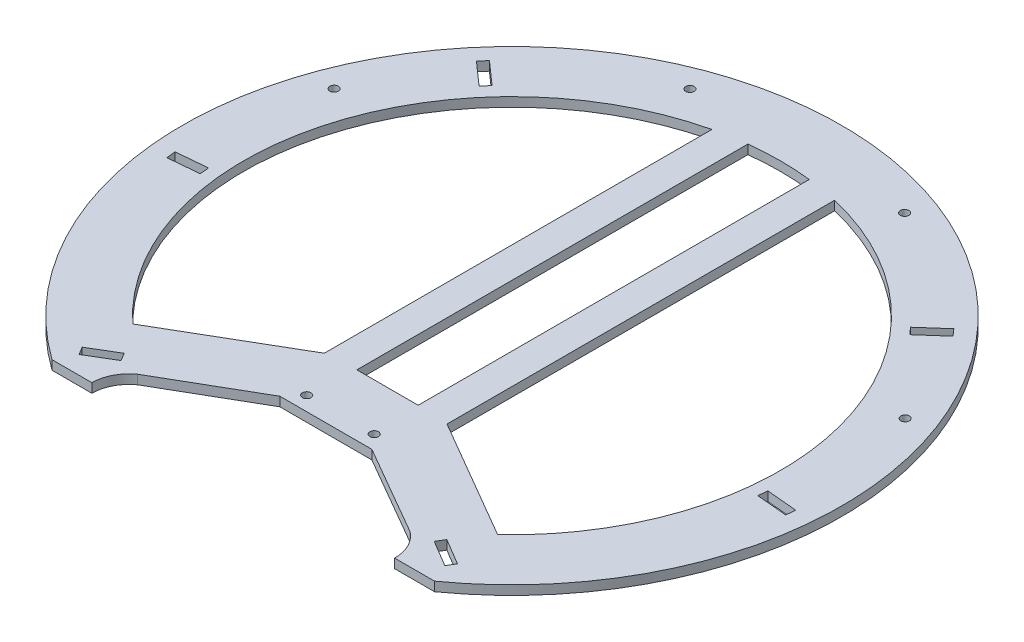
SolidWorks part; units mm, degrees
ref_plane "Front Plane" through (0, 0, 0) normal (0, 0, 1) x (1, 0, 0)
ref_plane "Top Plane" through (0, 0, 0) normal (0, 1, 0) x (1, 0, 0)
ref_plane "Right Plane" through (0, 0, 0) normal (1, 0, 0) x (0, 0, -1)
sketch "Sketch5" plane through (0, 0, 0) normal (0, 1, 0) x (1, 0, 0)
  line L1 (-49.5723, -87.4126) -> (-62.5723, -87.4126)
  line L93 (97.7677, -158.9337) -> (-112.9898, -158.9337) construction
  line L94 (-15.1046, -60.5872) -> (-44.5495, -77.5872)
  line L95 (-15.1046, -60.5872) -> (14.8954, -60.5872)
  line L96 (49.3277, -87.5872) -> (62.3277, -87.5872)
  line L97 (14.8954, -60.5872) -> (44.3402, -77.5872)
  line L102 (-59.4886, -64.1667) -> (-20, -41.1955)
  line L103 (-10, -40.5872) -> (10, -40.5872)
  line L104 (20, -41.1955) -> (59.4886, -64.1667)
  line L105 (-20, -41.1955) -> (-20, 85.1836)
  line L106 (-100.9, -11.655) -> (-101.1724, -8.6674)
  line L107 (-100.9, -11.655) -> (-90.9, -10.7432)
  line L108 (-101.1724, -8.6674) -> (-91.1724, -7.7556)
  line L109 (-90.9, -10.7432) -> (-91.1724, -7.7556)
  line L110 (-77.7028, 66.1084) -> (-75.7142, 68.3546)
  line L111 (-75.7142, 68.3546) -> (-68.2269, 61.7257)
  line L112 (-77.7028, 66.1084) -> (-70.2156, 59.4796)
  line L113 (-70.2156, 59.4796) -> (-68.2269, 61.7257)
  line L114 (0, -5.2132) -> (0, 128.8971) construction
  line L115 (77.7028, 66.1084) -> (75.7142, 68.3546)
  line L116 (75.7142, 68.3546) -> (68.2269, 61.7257)
  line L117 (70.2156, 59.4796) -> (68.2269, 61.7257)
  line L118 (77.7028, 66.1084) -> (70.2156, 59.4796)
  line L119 (100.9, -11.655) -> (90.9, -10.7432)
  line L120 (90.9, -10.7432) -> (91.1724, -7.7556)
  line L121 (101.1724, -8.6674) -> (91.1724, -7.7556)
  line L122 (100.9, -11.655) -> (101.1724, -8.6674)
  line L123 (-10, 86.9267) -> (-10, -40.5872)
  line L124 (20, -41.1955) -> (20, 85.1836)
  line L125 (10, 86.9267) -> (10, -40.5872)
  line L126 (-61.1798, -78.961) -> (-52.5926, -73.8364)
  line L127 (-52.5926, -73.8364) -> (-51.0553, -76.4126)
  line L128 (-51.0553, -76.4126) -> (-59.6424, -81.5372)
  line L129 (-59.6424, -81.5372) -> (-61.1798, -78.961)
  line L130 (52.5926, -73.8364) -> (51.0553, -76.4126)
  line L131 (61.1798, -78.961) -> (52.5926, -73.8364)
  line L132 (59.6424, -81.5372) -> (61.1798, -78.961)
  line L133 (51.0553, -76.4126) -> (59.6424, -81.5372)
  arc A21 (59.4886, -64.1667) -> (20, 85.1836) centre (0, 0) ccw
  arc A22 (-62.5723, -87.4126) -> (62.3277, -87.5872) centre (0, 0) cw
  arc A23 (-49.5723, -87.4126) -> (-44.5495, -77.5872) centre (-37.4508, -87.4126) cw
  arc A24 (49.3277, -87.5872) -> (44.3402, -77.5872) centre (36.8088, -87.5872) ccw
  circle A25 centre (-93.1034, 35.1) radius 1.4
  circle A26 centre (35, 93.0342) radius 1.4
  circle A29 centre (-35, 93.0342) radius 1.4
  circle A30 centre (93.1034, 35.1) radius 1.4
  circle A32 centre (-11, -55.9285) radius 1.4
  circle A33 centre (11, -55.9285) radius 1.4
  arc A34 (-20, 85.1836) -> (-59.4886, -64.1667) centre (0, 0) ccw
  arc A35 (10, 86.9267) -> (-10, 86.9267) centre (0, 0) ccw
  point P6 (-0.1046, -60.5872)
  point P30 (0, 0)
  point P31 (0, 0)
  dimension "D1" = 107.5
  dimension "D6" = 3
  dimension "D2" = 175
  dimension "D9" = 99.4
  dimension "D10" = 35
  dimension "D11" = 35.1
  dimension "D16" = 35.1
  dimension "D17" = 99.4
  dimension "D18" = 35
  dimension "D19" = 99.5
  dimension "D20" = 99.5
  dimension "D34" = 11
  dimension "D35" = 57
  dimension "D36" = 2.8
  dimension "D3" = 10
  dimension "D4" = 3
  dimension "D5" = 10
  dimension "D7" = 92
  dimension "D8" = 91.5
  dimension "D12" = 20
  dimension "D21" = 13
  dimension "D22" = 13
  dimension "D23" = 34
  dimension "D24" = 34
  dimension "D25" = 30
  dimension "D26" = 20
  dimension "D27" = 3
  dimension "D28" = 3
  dimension "D29" = 75.7142
  dimension "D30" = 101.1724
  dimension "D31" = 77.7028
  dimension "D32" = 100.9
  dimension "D33" = 91.1724
  dimension "D37" = 10
  dimension "D38" = 150
  dimension "D39" = 150
  dimension "D40" = 27
  dimension "D41" = 98.9
  dimension "D42" = 3
  dimension "D43" = 10
  dimension "D44" = 3
  dimension "D45" = 93
  dimension "D46" = 11
extrude "Boss-Extrude1" add sketch "Sketch5" along normal blind 3
